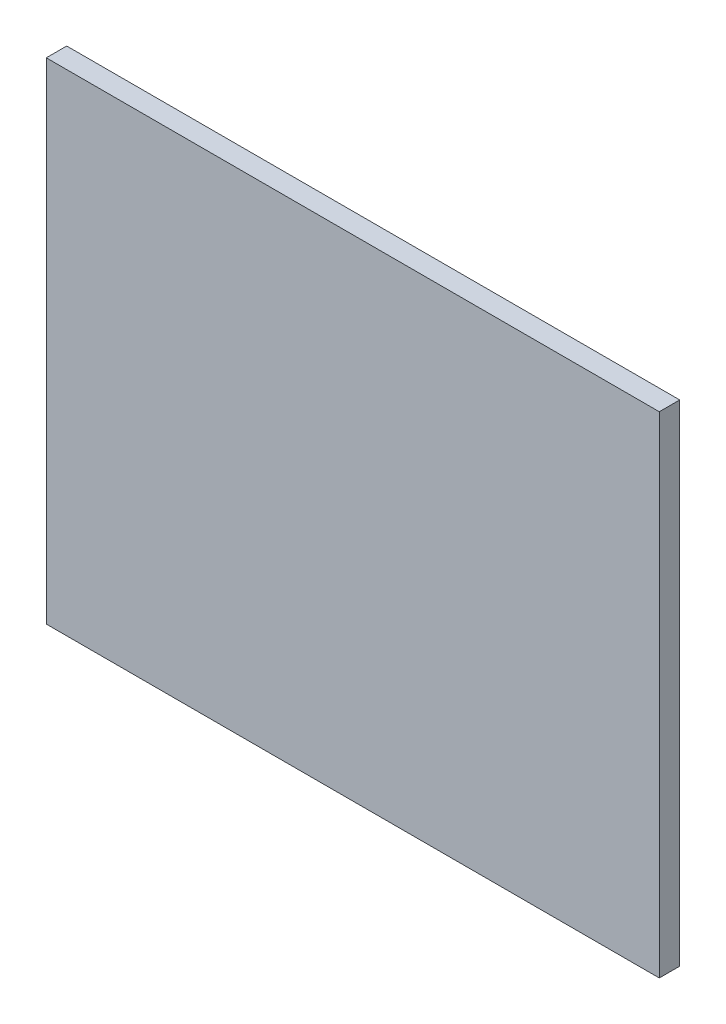
SolidWorks part; units mm, degrees
ref_plane "Front Plane" through (0, 0, 0) normal (0, 0, 1) x (1, 0, 0)
ref_plane "Top Plane" through (0, 0, 0) normal (0, 1, 0) x (1, 0, 0)
ref_plane "Right Plane" through (0, 0, 0) normal (1, 0, 0) x (0, 0, -1)
sketch "Sketch1" plane through (0, 0, 0) normal (0, 0, 1) x (1, 0, 0)
  line L1 (750, -600) -> (-750, -600)
  line L2 (750, -600) -> (750, 600)
  line L3 (750, 600) -> (-750, 600)
  line L4 (-750, -600) -> (-750, 600)
  line L5 (750, -600) -> (-750, 600) construction
  line L6 (750, 600) -> (-750, -600) construction
  point P0 (0, 0)
  dimension "D1" = 1500
  dimension "D2" = 1200
extrude "Boss-Extrude1" add sketch "Sketch1" along normal blind 50
